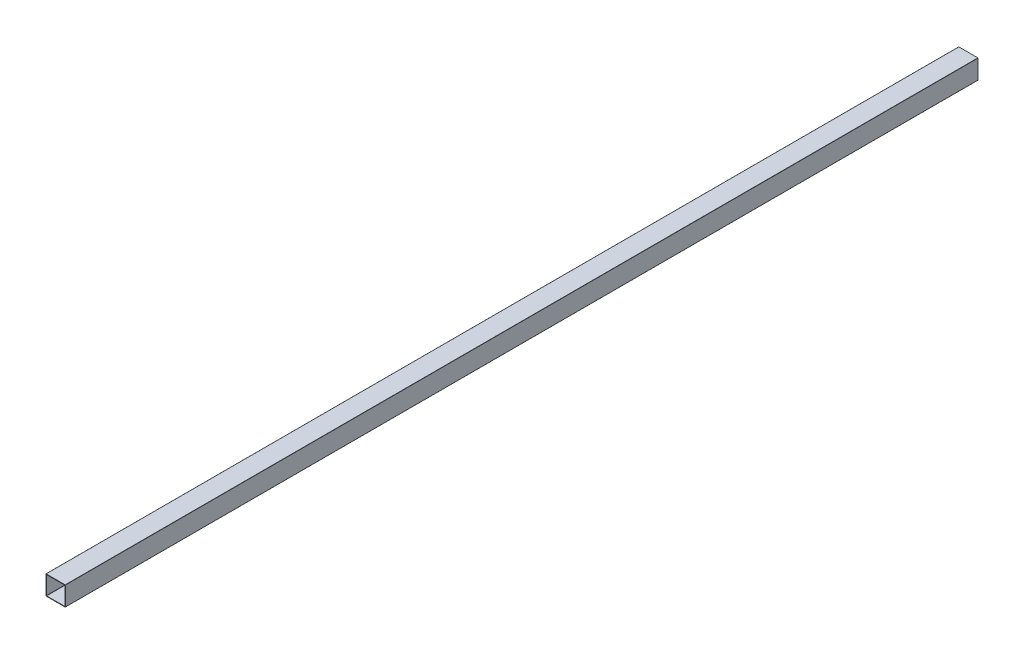
SolidWorks part; units mm, degrees
material "AISI 1035 Acero (SS)"
ref_plane "Alzado" through (0, 0, 0) normal (0, 0, 1) x (1, 0, 0)
ref_plane "Planta" through (0, 0, 0) normal (0, 1, 0) x (1, 0, 0)
ref_plane "Vista lateral" through (0, 0, 0) normal (1, 0, 0) x (0, 0, -1)
sketch "Croquis1" plane through (0, 0, 0) normal (0, 0, 1) x (1, 0, 0)
  line L0 (-60.46, -60.46) -> (-60.46, 60.46)
  line L1 (-63.5, -63.5) -> (63.5, -63.5)
  line L2 (-63.5, -63.5) -> (-63.5, 63.5)
  line L3 (-63.5, 63.5) -> (63.5, 63.5)
  line L4 (63.5, -63.5) -> (63.5, 63.5)
  line L5 (-63.5, -63.5) -> (63.5, 63.5) construction
  line L6 (-63.5, 63.5) -> (63.5, -63.5) construction
  line L7 (-60.46, 60.46) -> (60.46, 60.46)
  line L8 (60.46, -60.46) -> (60.46, 60.46)
  line L9 (-60.46, -60.46) -> (60.46, -60.46)
  point P0 (0, 0)
  dimension "D2" = 127
  dimension "D3" = 3.04
extrude "Saliente-Extruir1" add sketch "Croquis1" against normal blind 6000
fillet "Redondeo1" radius 1 8 edges at (-60.46, 60.46, -3000) (60.46, 60.46, -3000) (60.46, -60.46, -3000) (-63.5, -63.5, -3000) (-63.5, 63.5, -3000) (-60.46, -60.46, -3000) (63.5, -63.5, -3000) (63.5, 63.5, -3000)
